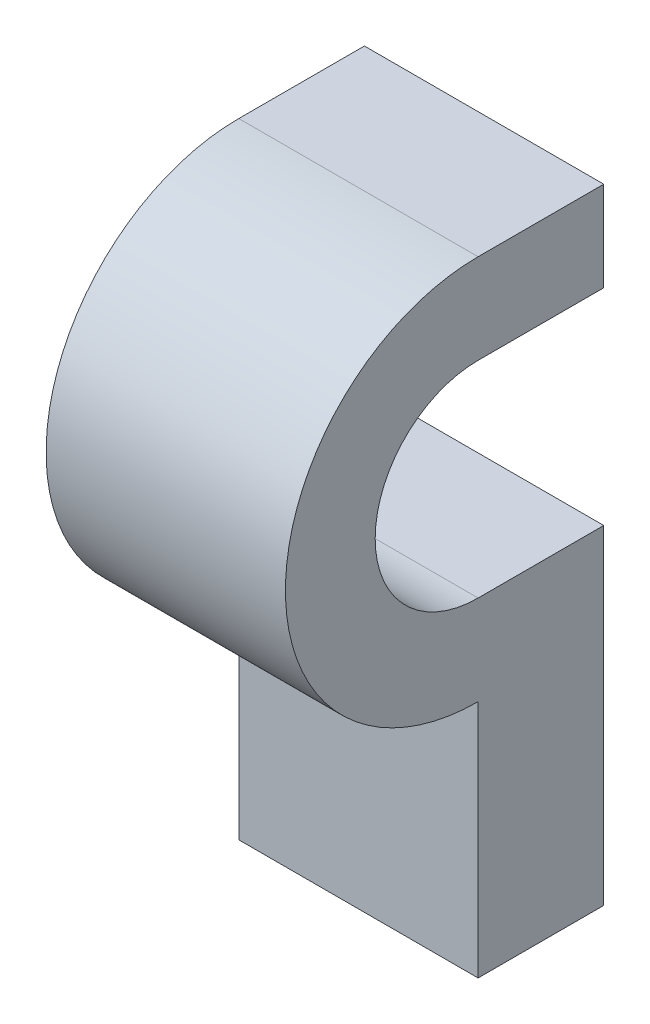
SolidWorks part; units mm, degrees
ref_plane "Front Plane" through (0, 0, 0) normal (0, 0, 1) x (1, 0, 0)
ref_plane "Top Plane" through (0, 0, 0) normal (0, 1, 0) x (1, 0, 0)
ref_plane "Right Plane" through (0, 0, 0) normal (1, 0, 0) x (0, 0, -1)
sketch "Sketch1" plane through (0, 0, 0) normal (1, 0, 0) x (0, 0, -1)
  line L0 (0, 1.381) -> (0, -9.619)
  line L1 (0, -9.619) -> (-4.2, -9.619)
  line L2 (-4.2, -9.619) -> (-4.2, -1.619)
  line L3 (0, 8.261) -> (0, 11.261)
  line L4 (0, 11.261) -> (-4.2, 11.261)
  line L5 (0, 8.261) -> (-4.2, 8.261)
  line L6 (0, 1.381) -> (-4.2, 1.381)
  arc A0 (-4.2, 1.381) -> (-4.2, 8.261) centre (-4.2, 4.821) cw
  arc A1 (-4.2, -1.619) -> (-4.2, 11.261) centre (-4.2, 4.821) cw
  dimension "D4" = 3.44
  dimension "D2" = 4.2
  dimension "D3" = 8
  dimension "D1" = 3
  dimension "D5" = 3
extrude "Boss-Extrude1" add sketch "Sketch1" along normal blind 8
sketch "ClampMountHoleSketch2" plane through (0, 0, 0) normal (0, 0, -1) x (-1, 0, 0)
  line L0 (-8, -9.619) -> (0, -9.619) construction
  line L1 (-8, -9.619) -> (-8, 1.381) construction
  circle A0 centre (-4, -5.619) radius 2
  dimension "D1" = 4
  dimension "D2" = 4
  dimension "D3" = 4
extrude "ClampMountHoleCut-Extrude1" cut sketch "ClampMountHoleSketch2" against normal blind 4.1
equation "\"M3HeatInsertHoleDepth\"= 4.1'Spec"
equation "\"D2@Sketch1\"=\"M3HeatInsertHoleDepth\" + .1mm"
equation "\"PowerCordClampBodyWidth\"= 8mm"
equation "\"PowerCordClampHookWidth\"= 3mm"
equation "\"M3HeatInsertHoleDiameter\"= 4mm"
equation "\"D1@Boss-Extrude1\"=\"PowerCordClampBodyWidth\""
equation "\"ClampBodyDepth\"=3"
equation "\"D1@Sketch1\"=\"ClampBodyDepth\""
equation "\"D5@Sketch1\"=\"ClampBodyDepth\""
equation "\"D3@Sketch1\"=\"M3HeatInsertHoleDiameter\"*2"
equation "\"D1@ClampMountHoleSketch2\"=\"M3HeatInsertHoleDiameter\""
equation "\"D2@ClampMountHoleSketch2\"=\"M3HeatInsertHoleDiameter\""
equation "\"D3@ClampMountHoleSketch2\"=\"PowerCordClampBodyWidth\"/2"
equation "\"D1@ClampMountHoleCut-Extrude1\"=\"M3HeatInsertHoleDepth\""
